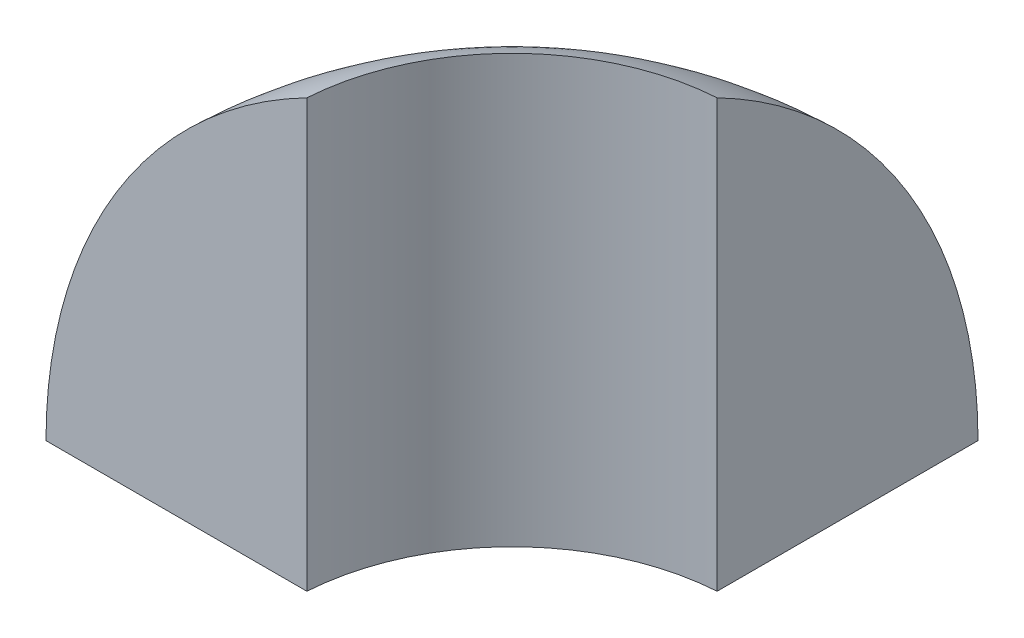
SolidWorks part; units mm, degrees
ref_plane "Front Plane" through (0, 0, 0) normal (0, 0, 1) x (1, 0, 0)
ref_plane "Top Plane" through (0, 0, 0) normal (0, 1, 0) x (1, 0, 0)
ref_plane "Right Plane" through (0, 0, 0) normal (1, 0, 0) x (0, 0, -1)
sketch "Sketch1" plane through (0, 0, 0) normal (0, 0, 1) x (1, 0, 0)
  line L0 (0, 16.6) -> (0, -16.6)
  arc A0 (0, 16.6) -> (0, -16.6) centre (0, 0) ccw
  dimension "D1" = 16.6
revolve "Revolve1" add sketch "Sketch1" angle 360 about L0
sketch "Sketch2" plane through (0, 0, 0) normal (0, 1, 0) x (1, 0, 0)
  line L0 (0, 16.8) -> (0, 0) construction
  line L1 (0, 0) -> (-16.8, 0) construction
  line L2 (-0.5, 16.5925) -> (-0.5, 0.5)
  line L3 (-0.5, 0.5) -> (-16.5925, 0.5)
  arc A2 (-16.5925, 0.5) -> (-0.5, 16.5925) centre (0, 0) ccw
  circle A3 centre (0, 0) radius 16.6 construction
  dimension "D1" = 0.5
  dimension "D2" = 0.5
extrude "Cut-Extrude1" cut sketch "Sketch2" against normal through all both and the other way through all
sketch "Sketch3" plane through (-0.5, 0, 0) normal (1, 0, 0) x (0, 0, -1)
  line L1 (0, 0) -> (19.8166, 0)
  line L2 (0, 0) -> (0, -17.6008)
  line L3 (0, -17.6008) -> (19.8166, -17.6008)
  line L4 (19.8166, 0) -> (19.8166, -17.6008)
extrude "Cut-Extrude2" cut sketch "Sketch3" against normal through all
sketch "Sketch6" plane through (0, 0, 0) normal (0, -1, 0) x (1, 0, 0)
  circle A0 centre (0, 0) radius 7.6
  dimension "D1" = 15.2
extrude "Cut-Extrude3" cut sketch "Sketch6" against normal through all
